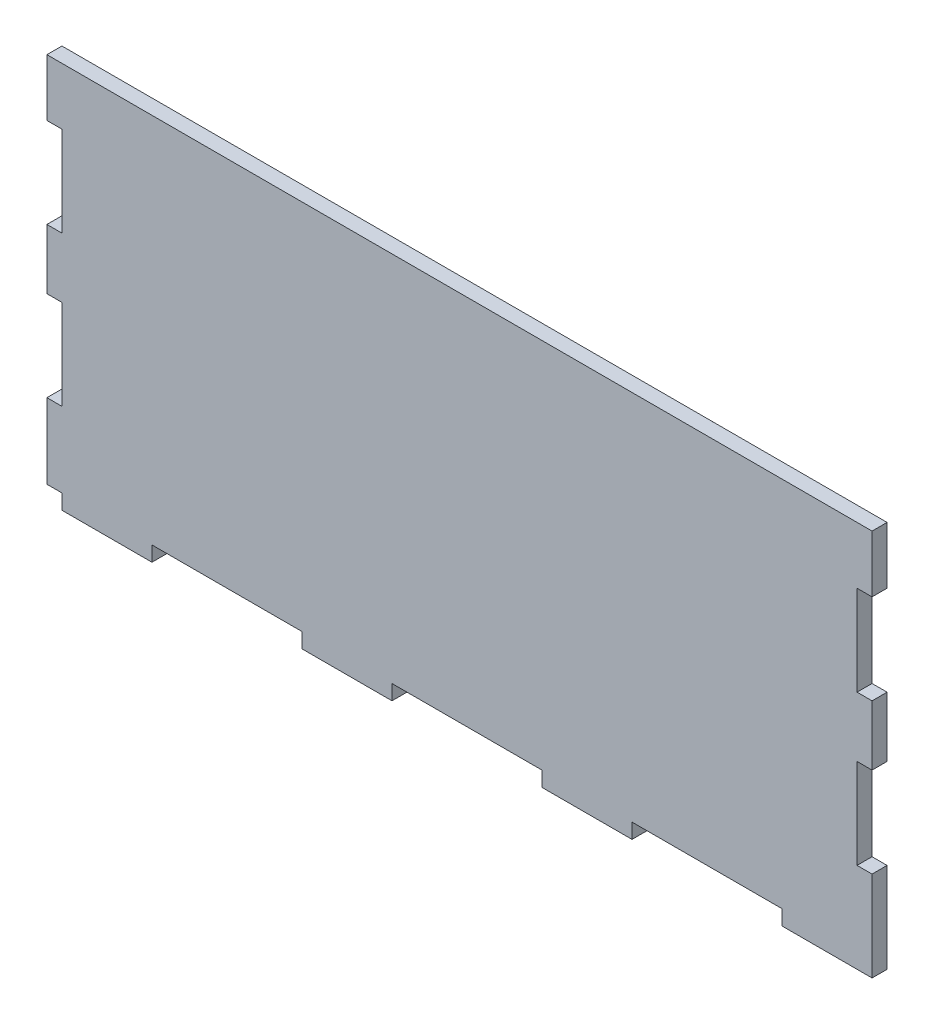
SolidWorks part; units mm, degrees
ref_plane "Front Plane" through (0, 0, 0) normal (0, 0, 1) x (1, 0, 0)
ref_plane "Top Plane" through (0, 0, 0) normal (0, 1, 0) x (1, 0, 0)
ref_plane "Right Plane" through (0, 0, 0) normal (1, 0, 0) x (0, 0, -1)
sketch "Sketch1" plane through (0, 0, 0) normal (0, 0, 1) x (1, 0, 0)
  line L6 (180, -99) -> (180, -69)
  line L15 (2000, 0) -> (0, 0) construction
  line L49 (180, -124) -> (180, -129)
  line L50 (180, -129) -> (210, -129)
  line L51 (210, -129) -> (210, -124)
  line L53 (260, -124) -> (260, -129)
  line L54 (260, -129) -> (290, -129)
  line L55 (290, -129) -> (290, -124)
  line L57 (340, -124) -> (340, -129)
  line L58 (340, -129) -> (370, -129)
  line L59 (370, -129) -> (370, -124)
  line L61 (420, -124) -> (420, -129)
  line L62 (420, -129) -> (450, -129)
  line L63 (450, -129) -> (450, -124)
  line L65 (180, 0) -> (450, 0)
  line L66 (450, 0) -> (450, -19)
  line L67 (210, -124) -> (260, -124)
  line L68 (290, -124) -> (340, -124)
  line L69 (370, -124) -> (420, -124)
  line L70 (450, -99) -> (450, -124)
  line L71 (450, -99) -> (445, -99)
  line L73 (450, -69) -> (445, -69)
  line L74 (445, -99) -> (445, -69)
  line L75 (450, -49) -> (445, -49)
  line L77 (450, -19) -> (445, -19)
  line L78 (445, -49) -> (445, -19)
  line L79 (450, -49) -> (450, -69)
  line L80 (315, 0) -> (315, -23.716) construction
  line L81 (310, 0) -> (310, -19) construction
  line L83 (180, -99) -> (175, -99)
  line L85 (180, -69) -> (175, -69)
  line L87 (180, -49) -> (175, -49)
  line L89 (180, -19) -> (175, -19)
  line L92 (180, -124) -> (175, -124)
  line L93 (175, -124) -> (175, -99)
  line L94 (180, -99) -> (180, -69)
  line L95 (175, -69) -> (175, -49)
  line L96 (175, -19) -> (175, 0)
  line L97 (175, 0) -> (180, 0)
  line L98 (180, -49) -> (180, -19)
  dimension "D1" = 30
  dimension "D2" = 5
  dimension "D3" = 30
  dimension "D4" = 30
  dimension "D5" = 5
  dimension "D6" = 20
  dimension "D7" = 5
  dimension "D8" = 30
  dimension "D9" = 5
  dimension "D10" = 30
  dimension "D11" = 30
  dimension "D12" = 5
  dimension "D13" = 20
  dimension "D14" = 5
  dimension "D15" = 5
  dimension "D16" = 135
extrude "Boss-Extrude1" add sketch "Sketch1" along normal blind 5 contours L98 L87 L95 L85 L6 L83 L93 L92 L49 L50 L51 L67 L53 L54 L55 L68 L57 L58 L59 L69 L61 L62 L63 L70 L71 L74 L73 L79 L75 L78 L77 L66 L65 L97 L96 L89
